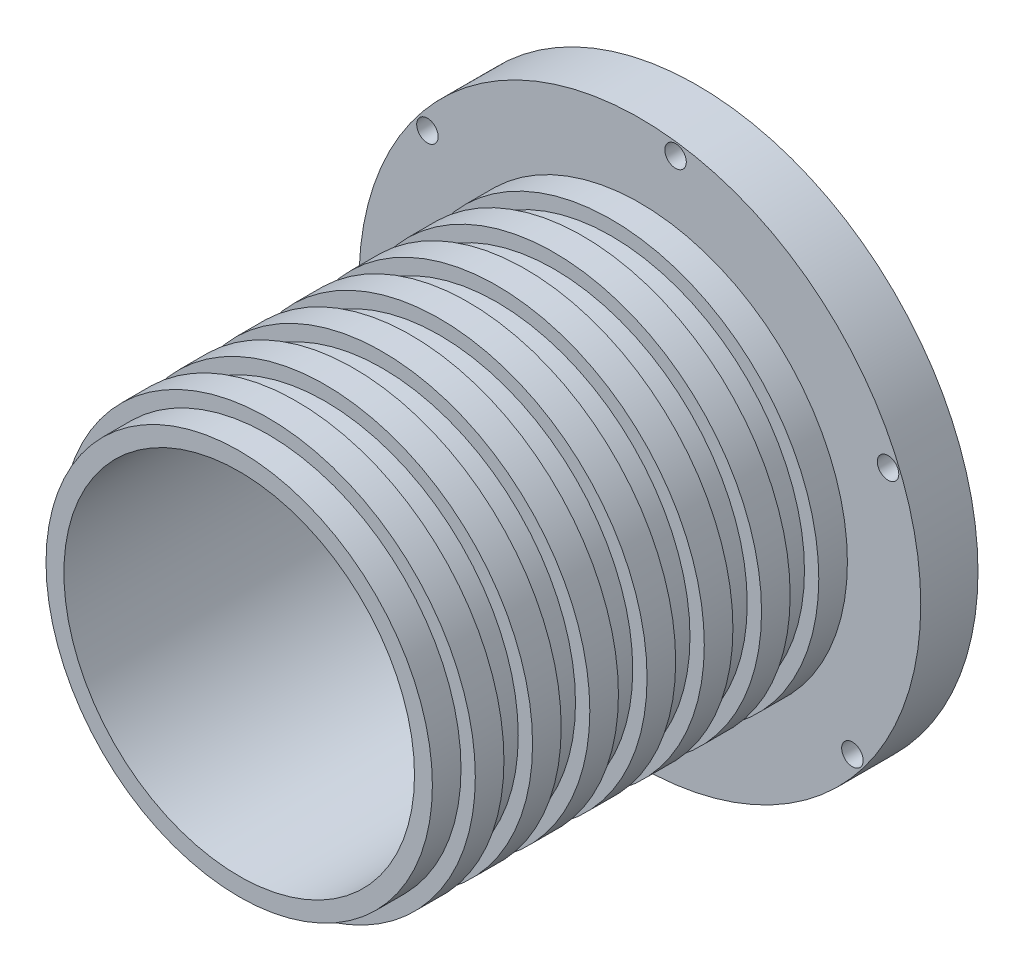
SolidWorks part; units mm, degrees
ref_plane "Front Plane" through (0, 0, 0) normal (0, 0, 1) x (1, 0, 0)
ref_plane "Top Plane" through (0, 0, 0) normal (0, 1, 0) x (1, 0, 0)
ref_plane "Right Plane" through (0, 0, 0) normal (1, 0, 0) x (0, 0, -1)
sketch "Sketch1" plane through (0, 0, 0) normal (0, 0, 1) x (1, 0, 0)
  circle A0 centre (0, 0) radius 28
  dimension "D1" = 56
extrude "Boss-Extrude1" add sketch "Sketch1" along normal blind 4
sketch "Sketch2" plane through (0, 0, 4) normal (0, 0, 1) x (1, 0, 0)
  circle A1 centre (0, 0) radius 39.25
  dimension "D1" = 78.5
extrude "Boss-Extrude2" add sketch "Sketch2" along normal blind 8
sketch "Sketch3" plane through (0, 0, 4) normal (0, 0, -1) x (-1, 0, 0)
  circle A0 centre (0, 0) radius 37.5
  circle A1 centre (3.4108, 37.3446) radius 1.5
  circle A2 centre (34.0467, 15.7184) radius 1.5
  circle A3 centre (30.6359, -21.6261) radius 1.5
  circle A4 centre (-3.4108, -37.3446) radius 1.5
  circle A5 centre (-34.0467, -15.7184) radius 1.5
  circle A6 centre (-30.6359, 21.6261) radius 1.5
  point P17 (0, 0)
  circle M2 centre (0, 0) radius 39.25
  dimension "D1" = 75
  dimension "D2" = 3
  dimension "D3" = 6
extrude "Cut-Extrude1" [suppressed] cut sketch "Sketch3" against normal through all contours A0 A6 M2 | A0 A6 | A1 A0 M2 | A0 A1 | A2 A0 M2 | A0 A2 | A3 A0 M2 | A0 A3 | A0 A4 M2 | A5 M2 | A0 A5 | A0 A5 M2
sketch "Sketch4" plane through (0, 0, 12) normal (0, 0, 1) x (1, 0, 0)
  circle A0 centre (0, 0) radius 27
  dimension "D1" = 54
extrude "Boss-Extrude3" add sketch "Sketch4" along normal blind 56
sketch "Sketch5" plane through (0, 0, 68) normal (0, 0, 1) x (1, 0, 0)
  circle A0 centre (0, 0) radius 24.5
  dimension "D1" = 49
extrude "Cut-Extrude2" cut sketch "Sketch5" against normal through all
sketch "Sketch6" plane through (0, 0, 12) normal (0, 0, 1) x (1, 0, 0)
  circle A0 centre (0, 0) radius 29
  dimension "D1" = 58
extrude "Boss-Extrude4" add sketch "Sketch6" along normal blind 4
sketch "Sketch7" plane through (0, 0, 16) normal (0, 0, 1) x (1, 0, 0)
  circle A0 centre (0, 0) radius 28
pattern_linear "LPattern1" count 7 spacing 8 along (0, 0, 1) of "Boss-Extrude4"
sketch "Sketch8" plane through (0, 0, 12) normal (0, 0, 1) x (1, 0, 0)
  circle A0 centre (0, 0) radius 37.5
  circle A1 centre (4.9852, 37.1672) radius 1.5
  dimension "D1" = 75
  dimension "D2" = 3
extrude "Cut-Extrude3" cut sketch "Sketch8" against normal through all contours A0 A1 | A0 A1
pattern_circular "CirPattern1" count 6 over 360 about axis through (0, 0, 0) along (0, 0, 1) of "Cut-Extrude3"
sketch "Sketch9" plane through (0, 0, 64) normal (0, 0, 1) x (1, 0, 0)
  circle A0 centre (0, 0) radius 24.5
  dimension "D1" = 49
extrude "Cut-Extrude4" cut sketch "Sketch9" against normal through all
